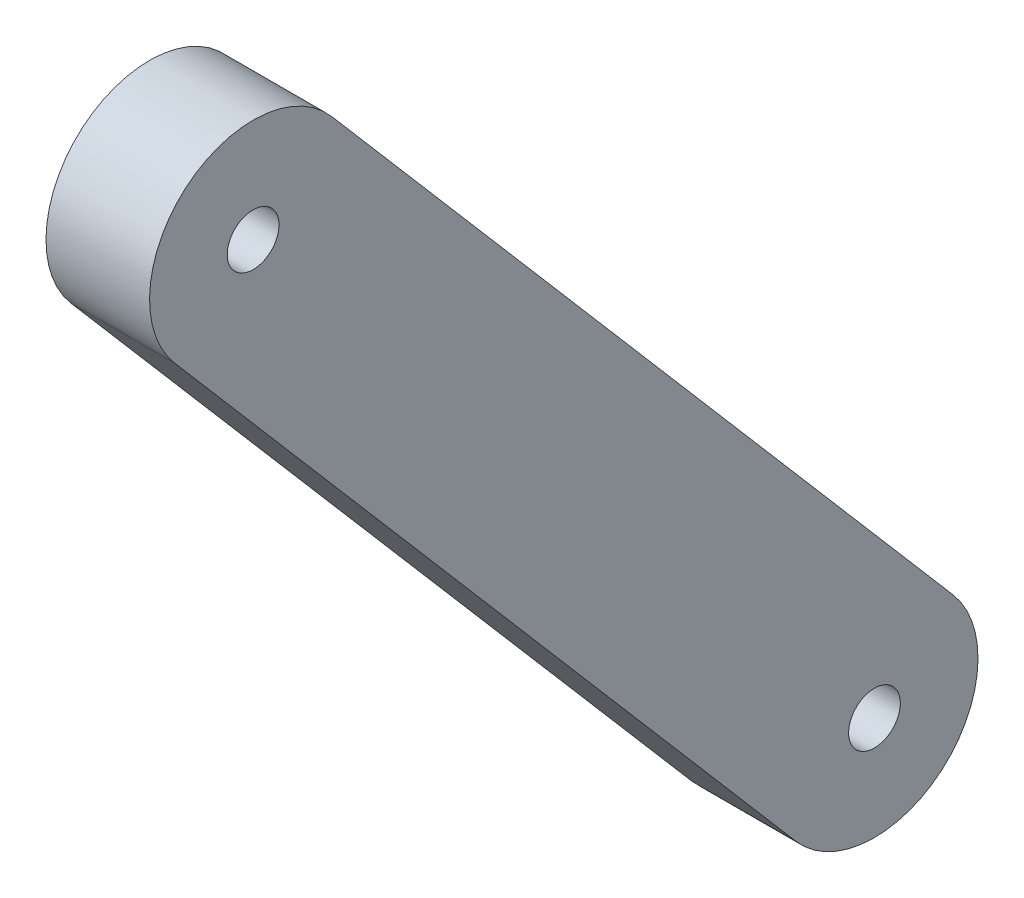
SolidWorks part; units mm, degrees
ref_plane "Front Plane" through (0, 0, 0) normal (0, 0, 1) x (1, 0, 0)
ref_plane "Top Plane" through (0, 0, 0) normal (0, 1, 0) x (1, 0, 0)
ref_plane "Right Plane" through (0, 0, 0) normal (1, 0, 0) x (0, 0, -1)
sketch "Sketch1" plane through (0, 0, 0) normal (1, 0, 0) x (0, 0, -1)
  line L0 (0, 0) -> (-300, 350) construction
  line L1 (-37.9628, -32.5396) -> (-337.9628, 317.4604)
  line L2 (37.9628, 32.5396) -> (-262.0372, 382.5396)
  arc A0 (-37.9628, -32.5396) -> (37.9628, 32.5396) centre (0, 0) ccw
  arc A1 (-262.0372, 382.5396) -> (-337.9628, 317.4604) centre (-300, 350) ccw
  circle A2 centre (-300, 350) radius 12.5
  circle A3 centre (0, 0) radius 12.5
  point P3 (-150, 175)
  dimension "D4" = 25
  dimension "D1" = 300
  dimension "D2" = 350
  dimension "D3" = 100
extrude "Boss-Extrude1" add sketch "Sketch1" along normal blind 50
